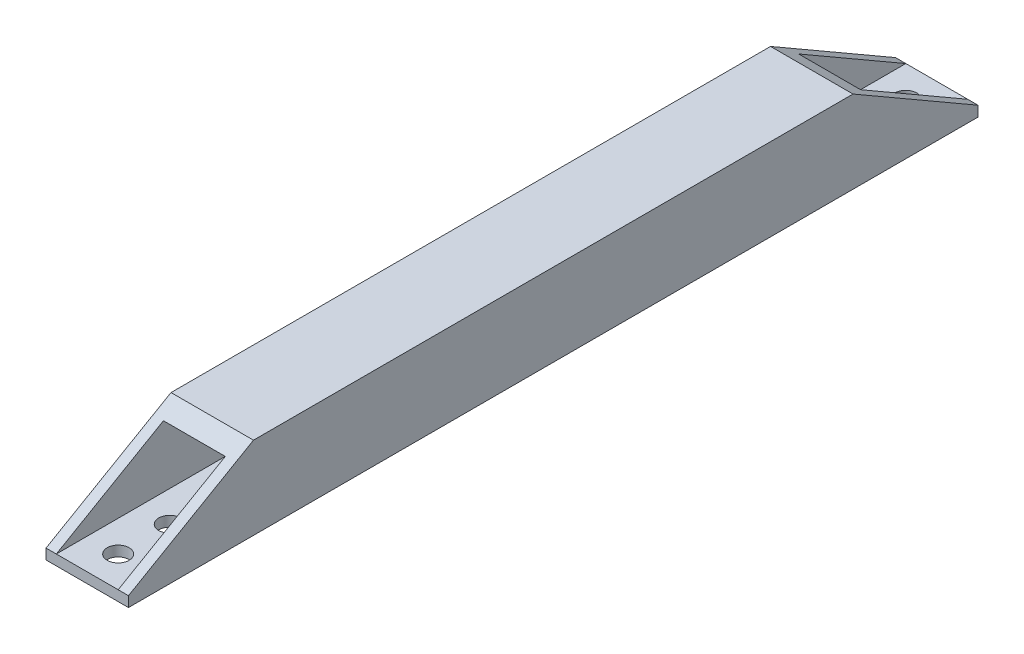
SolidWorks part; units mm, degrees
ref_plane "Front Plane" through (0, 0, 0) normal (0, 0, 1) x (1, 0, 0)
ref_plane "Top Plane" through (0, 0, 0) normal (0, 1, 0) x (1, 0, 0)
ref_plane "Right Plane" through (0, 0, 0) normal (1, 0, 0) x (0, 0, -1)
sketch "Sketch1" plane through (0, 0, 0) normal (0, 0, 1) x (1, 0, 0)
  line L1 (-9.525, -9.525) -> (9.525, -9.525)
  line L2 (-9.525, -9.525) -> (-9.525, 9.525)
  line L3 (-9.525, 9.525) -> (9.525, 9.525)
  line L4 (9.525, -9.525) -> (9.525, 9.525)
  line L5 (-9.525, -9.525) -> (9.525, 9.525) construction
  line L6 (-9.525, 9.525) -> (9.525, -9.525) construction
  line L7 (-12.7, -12.7) -> (12.7, -12.7)
  line L8 (-12.7, -12.7) -> (-12.7, 12.7)
  line L9 (-12.7, 12.7) -> (12.7, 12.7)
  line L10 (12.7, -12.7) -> (12.7, 12.7)
  line L11 (-12.7, -12.7) -> (12.7, 12.7) construction
  line L12 (-12.7, 12.7) -> (12.7, -12.7) construction
  point P0 (0, 0)
  point P6 (0, 0)
  dimension "D1" = 25.4
  dimension "D2" = 25.4
  dimension "D3" = 3.175
  dimension "D4" = 3.175
extrude "Boss-Extrude1" add sketch "Sketch1" along normal blind 261.62
sketch "Sketch2" plane through (12.7, 0, 0) normal (1, 0, 0) x (0, 0, -1)
  line L0 (-223.1252, 12.7) -> (-261.62, -9.525)
  line L1 (-261.62, 12.7) -> (0, 12.7) construction
  line L2 (-261.62, -12.7) -> (-261.62, 12.7) construction
  line L3 (-261.62, -12.7) -> (0, -12.7) construction
  line L4 (-130.81, -12.7) -> (-130.81, 12.7) construction
  line L5 (-38.4948, 12.7) -> (0, -9.525)
  line L6 (-261.62, -9.525) -> (-261.62, 12.7)
  line L7 (-261.62, 12.7) -> (-223.1252, 12.7)
  line L8 (-38.4948, 12.7) -> (0, 12.7)
  line L9 (0, 12.7) -> (0, -9.525)
  dimension "D1" = 3.175
  dimension "D2" = 30
extrude "Cut-Extrude2" cut sketch "Sketch2" against normal through all
sketch "Sketch3" plane through (0, -12.7, 0) normal (0, -1, 0) x (1, 0, 0)
  line L4 (0, 261.62) -> (0, 0) construction
  line L5 (12.7, 130.81) -> (-12.7, 130.81) construction
  line L8 (-12.7, 0) -> (12.7, 0)
  line L9 (12.7, 0) -> (12.7, 261.62)
  line L10 (12.7, 261.62) -> (-12.7, 261.62)
  line L11 (-12.7, 261.62) -> (-12.7, 0)
  line L12 (-12.7, 0) -> (12.7, 0)
  line L13 (12.7, 0) -> (12.7, 261.62)
  line L14 (12.7, 261.62) -> (-12.7, 261.62)
  line L15 (-12.7, 261.62) -> (-12.7, 0)
  circle A0 centre (0, 252.095) radius 3.3734
  circle A1 centre (0, 236.22) radius 3.3734
  circle A2 centre (0, 9.525) radius 3.3734
  circle A3 centre (0, 25.4) radius 3.3734
  dimension "D4" = 6.7469
  dimension "D2" = 9.525
  dimension "D3" = 15.875
  dimension "D1" = 0
extrude "Cut-Extrude3" cut sketch "Sketch3" against normal through all contours A0 | A1 | A3 | A2
